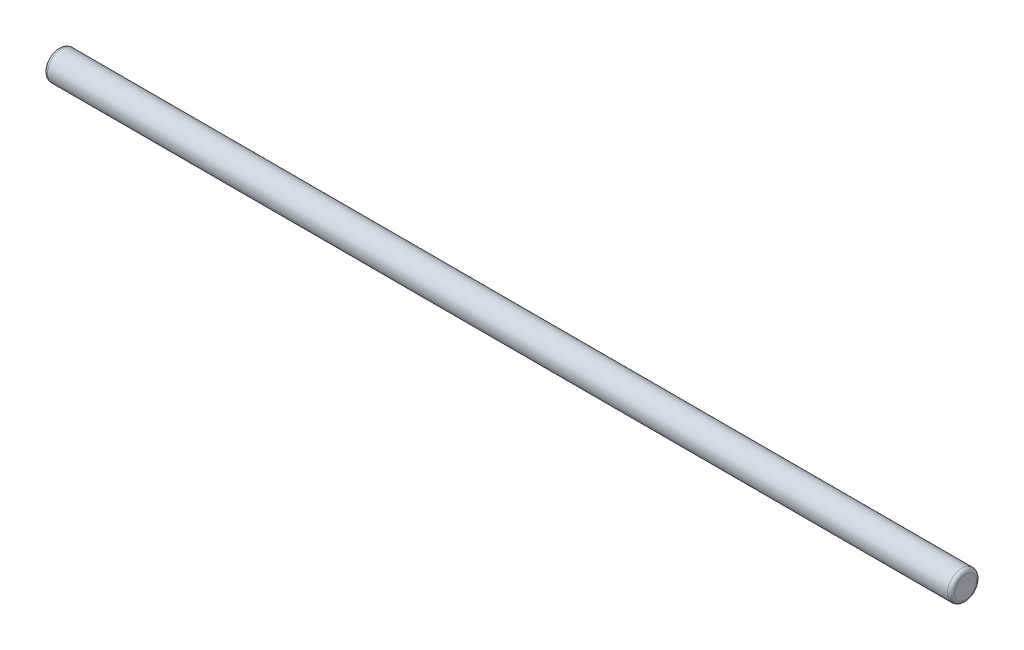
SolidWorks part; units mm, degrees
ref_plane "Front Plane" through (0, 0, 0) normal (0, 0, 1) x (1, 0, 0)
ref_plane "Top Plane" through (0, 0, 0) normal (0, 1, 0) x (1, 0, 0)
ref_plane "Right Plane" through (0, 0, 0) normal (1, 0, 0) x (0, 0, -1)
sketch "ProfileSketch1" plane through (0, 0, 0) normal (1, 0, 0) x (0, 0, -1)
  circle A0 centre (0, 0) radius 4
  dimension "D1" = 8
extrude "ProfileBoss-Extrude1" add sketch "ProfileSketch1" along normal blind 250
fillet "Fillet1" radius 1 2 edges at (0, 0, -4) (250, 0, -4)
equation "\"RodShaft8mmDiameter\"= 8mm"
equation "\"RodShaft250mmLength\"= 250mm"
equation "\"D1@ProfileBoss-Extrude1\" = \"RodShaft250mmLength\""
equation "\"D1@ProfileSketch1\"=\"RodShaft8mmDiameter\""
